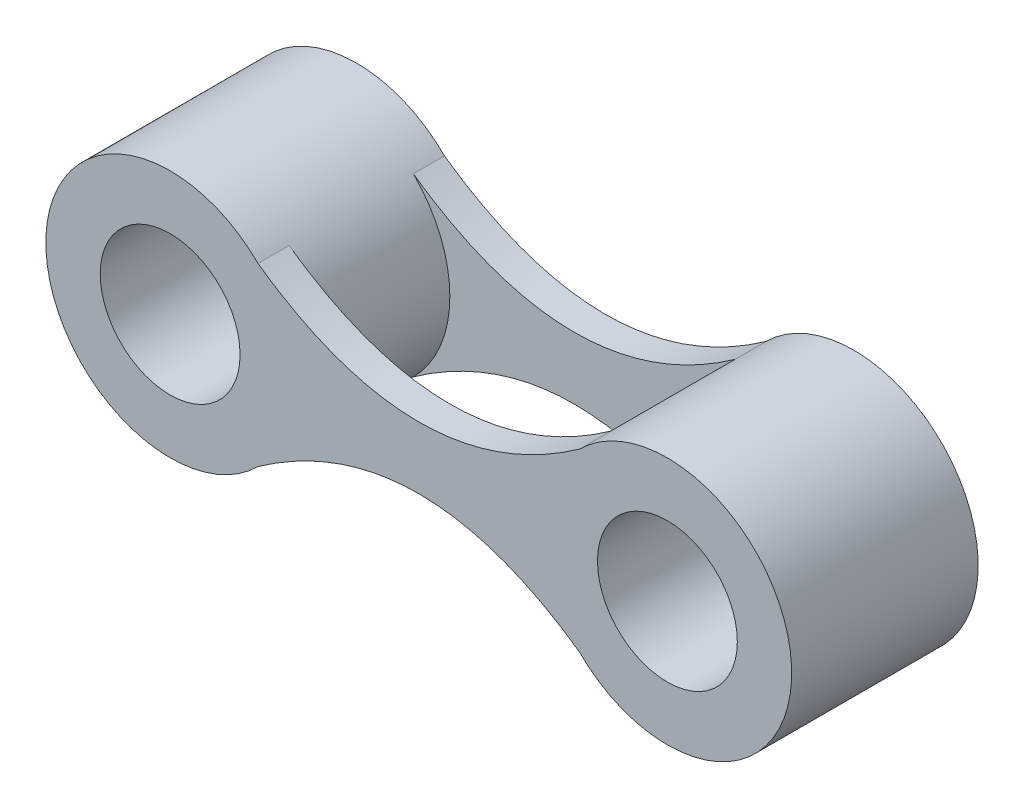
SolidWorks part; units mm, degrees
ref_plane "Front Plane" through (0, 0, 0) normal (0, 0, 1) x (1, 0, 0)
ref_plane "Top Plane" through (0, 0, 0) normal (0, 1, 0) x (1, 0, 0)
ref_plane "Right Plane" through (0, 0, 0) normal (1, 0, 0) x (0, 0, -1)
sketch "Sketch1" plane through (0, 0, 0) normal (0, 0, 1) x (1, 0, 0)
  line L0 (-6.35, 0) -> (6.35, 0) construction
  line L1 (-6.35, 0) -> (-6.35, 5.3941) construction
  line L2 (0, -9.5021) -> (0, 10.9777) construction
  line L3 (-6.35, 0) -> (0, 6.35) construction
  line L4 (0, 6.35) -> (6.35, 0) construction
  line L5 (-2.1004, 0.7937) -> (1.9982, 0.7937) construction
  arc A0 (-4.1049, 2.2451) -> (-4.1049, -2.2451) centre (-6.35, 0) ccw
  arc A1 (4.1049, -2.2451) -> (4.1049, 2.2451) centre (6.35, 0) ccw
  spline S0 degree 2 poles (-4.1049, 2.2451) (0, -0.6576) (4.1049, 2.2451) knots 0 0 0 1 1 1
  spline S1 degree 2 poles (-4.1049, -2.2451) (0, 0.6576) (4.1049, -2.2451) knots 0 0 0 1 1 1
  point P7 (-4.1049, 2.2451)
  point P12 (4.1049, 2.2451)
  dimension "D1" = 6.35
  dimension "D2" = 6.35
  dimension "D3" = 12.7
  dimension "D4" = 0.7937
extrude "Boss-Extrude1" add sketch "Sketch1" along normal blind 0.7937
ref_plane "chainplane" through (0, 0, 2.3812) normal (0, 0, 1) x (1, 0, 0)
sketch "Sketch2" plane through (0, 0, 0.7937) normal (0, 0, 1) x (1, 0, 0)
  circle A0 centre (-6.35, 0) radius 3.175
  circle A1 centre (6.35, 0) radius 3.175
extrude "Boss-Extrude2" add sketch "Sketch2" along normal blind 3.175
mirror "Mirror1" about plane through (0, 0, 2.3812) normal (0, 0, 1) of "Boss-Extrude1"
sketch "Sketch3" plane through (0, 0, 0) normal (0, 0, -1) x (-1, 0, 0)
  circle A0 centre (-6.35, 0) radius 1.7859
  circle A1 centre (6.35, 0) radius 1.7859
  dimension "D1" = 3.5719
  dimension "D2" = 3.5719
extrude "Cut-Extrude1" cut sketch "Sketch3" against normal blind 6.35
equation "\"large_diameter\" = 1/4in"
equation "\"small_diameter\" = 1/8in"
equation "\"arc_height\" = 1/32in"
equation "\"chain_space\" = 1/2in"
equation "\"chain_thickness\" = 1/32in"
equation "\"outer_height\" = 3/16in"
equation "\"inner_height\" = 2/16in"
equation "\"D1@Sketch1\" = \"large_diameter\""
equation "\"D2@Sketch1\" = \"large_diameter\""
equation "\"D3@Sketch1\"= \"chain_space\""
equation "\"D4@Sketch1\"= \"arc_height\""
equation "\"D1@Boss-Extrude1\"=\"chain_thickness\"\""
equation "\"D1@chainplane\" = \"inner_height\" / 2"
equation "\"D1@Boss-Extrude2\"= \"inner_height\""
equation "\"D1@Sketch3\" = \"small_diameter\" + \"give\""
equation "\"D2@Sketch3\" = \"small_diameter\" + \"give\""
equation "\"D1@Cut-Extrude1\"=\"inner_height\"*2"
equation "\"give\" = 1/64in"
